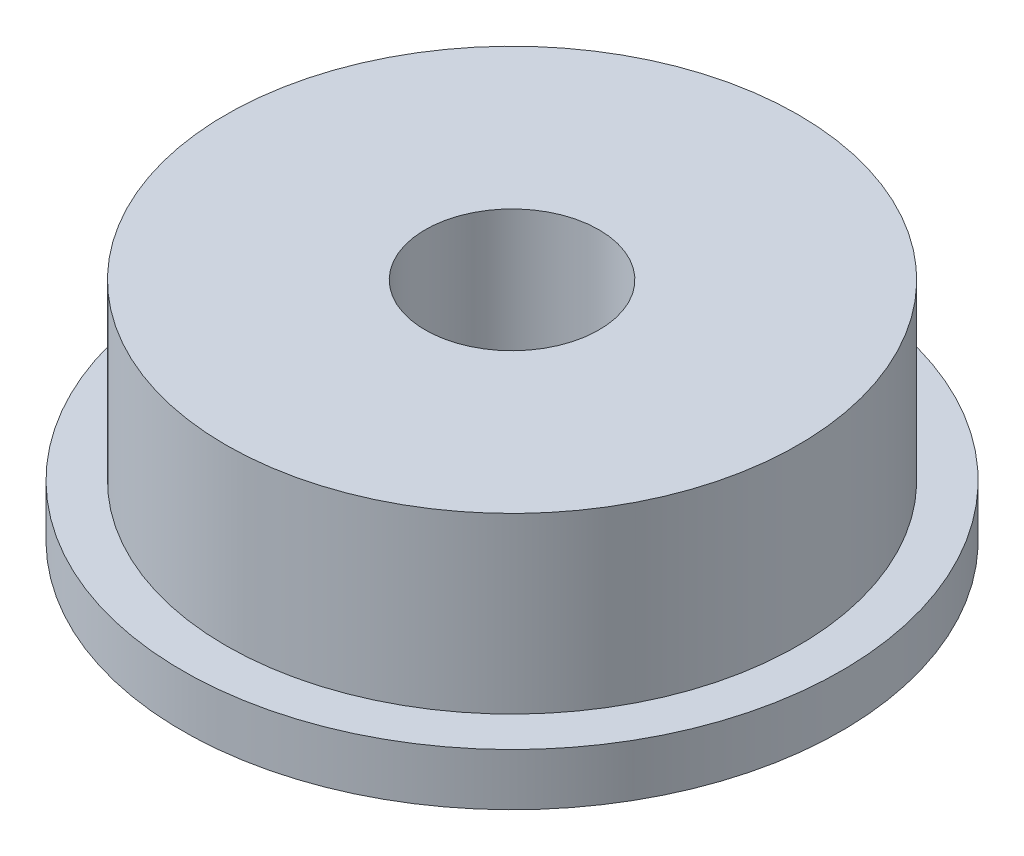
SolidWorks part; units mm, degrees
ref_plane "Plano frontal" through (0, 0, 0) normal (0, 0, 1) x (1, 0, 0)
ref_plane "Plano superior" through (0, 0, 0) normal (0, 1, 0) x (1, 0, 0)
ref_plane "Plano direito" through (0, 0, 0) normal (1, 0, 0) x (0, 0, -1)
sketch "Esboço1" plane through (0, 0, 0) normal (0, 0, 1) x (1, 0, 0)
  line L0 (1.5, 0) -> (1.5, 3.9)
  line L1 (1.5, 3.9) -> (4.94, 3.9)
  line L2 (4.94, 3.9) -> (4.94, 0.9)
  line L3 (4.94, 0.9) -> (5.69, 0.9)
  line L4 (5.69, 0.9) -> (5.69, 0)
  line L5 (5.69, 0) -> (1.5, 0)
  line L6 (0, 0) -> (0, 2.2451) construction
  dimension "D1" = 9.88
  dimension "D2" = 11.38
  dimension "D3" = 0.9
  dimension "D4" = 3.9
  dimension "D5" = 3
revolve "Revolução1" add sketch "Esboço1" angle 360 about L6
